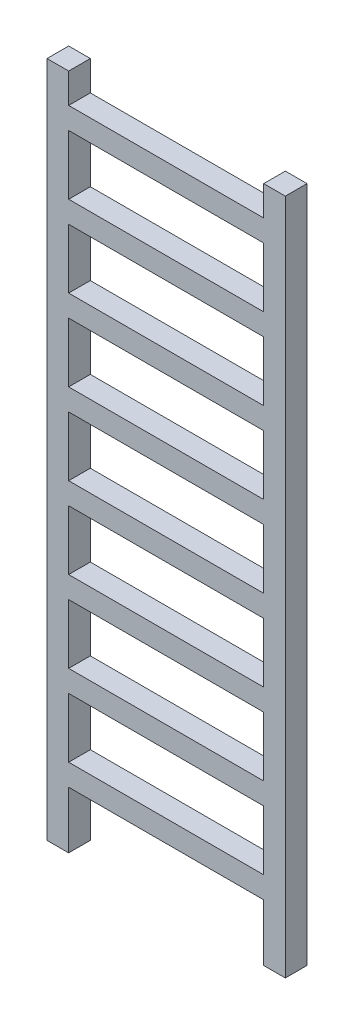
SolidWorks part; units mm, degrees
ref_plane "前视基准面" through (0, 0, 0) normal (0, 0, 1) x (1, 0, 0)
ref_plane "上视基准面" through (0, 0, 0) normal (0, 1, 0) x (1, 0, 0)
ref_plane "右视基准面" through (0, 0, 0) normal (1, 0, 0) x (0, 0, -1)
other "Configuration Table"
sketch "草图1" plane through (0, 0, 0) normal (0, 0, 1) x (1, 0, 0)
  line L1 (-440, -1250) -> (-360, -1250)
  line L2 (-440, -1250) -> (-440, 1250)
  line L3 (-440, 1250) -> (-360, 1250)
  line L4 (-360, -1250) -> (-360, 1250)
  line L5 (-440, -1250) -> (-360, 1250) construction
  line L6 (-440, 1250) -> (-360, -1250) construction
  point P0 (-400, 0)
extrude "凸台-拉伸1" add sketch "草图1" along normal blind 80
sketch "草图2" plane through (0, 0, 0) normal (0, 0, 1) x (1, 0, 0)
  line L1 (360, -1250) -> (440, -1250)
  line L2 (360, -1250) -> (360, 1250)
  line L3 (360, 1250) -> (440, 1250)
  line L4 (440, -1250) -> (440, 1250)
  line L5 (360, -1250) -> (440, 1250) construction
  line L6 (360, 1250) -> (440, -1250) construction
  point P0 (400, 0)
extrude "凸台-拉伸2" add sketch "草图2" along normal blind 80
sketch "草图3" plane through (0, 0, 0) normal (0, 0, 1) x (1, 0, 0)
  line L1 (-400, 1060) -> (400, 1060)
  line L2 (-400, 1060) -> (-400, 1140)
  line L3 (-400, 1140) -> (400, 1140)
  line L4 (400, 1060) -> (400, 1140)
  line L5 (-400, 1060) -> (400, 1140) construction
  line L6 (-400, 1140) -> (400, 1060) construction
  point P0 (0, 1100)
extrude "凸台-拉伸3" add sketch "草图3" along normal blind 80
sketch "草图4" plane through (0, 0, 0) normal (0, 0, 1) x (1, 0, 0)
  line L1 (-400, 760) -> (400, 760)
  line L2 (-400, 760) -> (-400, 840)
  line L3 (-400, 840) -> (400, 840)
  line L4 (400, 760) -> (400, 840)
  line L5 (-400, 760) -> (400, 840) construction
  line L6 (-400, 840) -> (400, 760) construction
  point P0 (0, 800)
extrude "凸台-拉伸4" add sketch "草图4" along normal blind 80
sketch "草图5" plane through (0, 0, 0) normal (0, 0, 1) x (1, 0, 0)
  line L1 (-400, 460) -> (400, 460)
  line L2 (-400, 460) -> (-400, 540)
  line L3 (-400, 540) -> (400, 540)
  line L4 (400, 460) -> (400, 540)
  line L5 (-400, 460) -> (400, 540) construction
  line L6 (-400, 540) -> (400, 460) construction
  point P0 (0, 500)
extrude "凸台-拉伸5" add sketch "草图5" along normal blind 80
sketch "草图6" plane through (0, 0, 0) normal (0, 0, 1) x (1, 0, 0)
  line L1 (-400, 160) -> (400, 160)
  line L2 (-400, 160) -> (-400, 240)
  line L3 (-400, 240) -> (400, 240)
  line L4 (400, 160) -> (400, 240)
  line L5 (-400, 160) -> (400, 240) construction
  line L6 (-400, 240) -> (400, 160) construction
  point P0 (0, 200)
extrude "凸台-拉伸6" add sketch "草图6" along normal blind 80
sketch "草图7" plane through (0, 0, 0) normal (0, 0, 1) x (1, 0, 0)
  line L1 (-400, -140) -> (400, -140)
  line L2 (-400, -140) -> (-400, -60)
  line L3 (-400, -60) -> (400, -60)
  line L4 (400, -140) -> (400, -60)
  line L5 (-400, -140) -> (400, -60) construction
  line L6 (-400, -60) -> (400, -140) construction
  point P0 (0, -100)
extrude "凸台-拉伸7" add sketch "草图7" along normal blind 80
sketch "草图8" plane through (0, 0, 0) normal (0, 0, 1) x (1, 0, 0)
  line L1 (-400, -440) -> (400, -440)
  line L2 (-400, -440) -> (-400, -360)
  line L3 (-400, -360) -> (400, -360)
  line L4 (400, -440) -> (400, -360)
  line L5 (-400, -440) -> (400, -360) construction
  line L6 (-400, -360) -> (400, -440) construction
  point P0 (0, -400)
extrude "凸台-拉伸8" add sketch "草图8" along normal blind 80
sketch "草图9" plane through (0, 0, 0) normal (0, 0, 1) x (1, 0, 0)
  line L1 (-400, -740) -> (400, -740)
  line L2 (-400, -740) -> (-400, -660)
  line L3 (-400, -660) -> (400, -660)
  line L4 (400, -740) -> (400, -660)
  line L5 (-400, -740) -> (400, -660) construction
  line L6 (-400, -660) -> (400, -740) construction
  point P0 (0, -700)
extrude "凸台-拉伸9" add sketch "草图9" along normal blind 80
sketch "草图10" plane through (0, 0, 0) normal (0, 0, 1) x (1, 0, 0)
  line L1 (-400, -1040) -> (400, -1040)
  line L2 (-400, -1040) -> (-400, -960)
  line L3 (-400, -960) -> (400, -960)
  line L4 (400, -1040) -> (400, -960)
  line L5 (-400, -1040) -> (400, -960) construction
  line L6 (-400, -960) -> (400, -1040) construction
  point P0 (0, -1000)
extrude "凸台-拉伸10" add sketch "草图10" along normal blind 80
